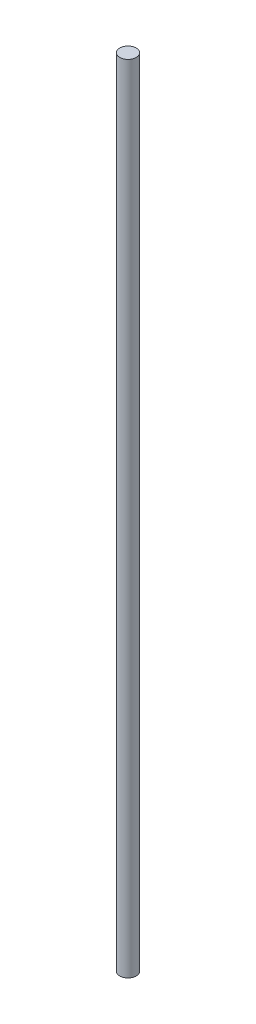
SolidWorks part; units mm, degrees
material "Alloy Steel"
ref_plane "Front Plane" through (0, 0, 0) normal (0, 0, 1) x (1, 0, 0)
ref_plane "Top Plane" through (0, 0, 0) normal (0, 1, 0) x (1, 0, 0)
ref_plane "Right Plane" through (0, 0, 0) normal (1, 0, 0) x (0, 0, -1)
sketch "Sketch1" plane through (0, 0, 0) normal (0, 1, 0) x (1, 0, 0)
  circle A0 centre (0, 0) radius 4.125
  dimension "D1" = 8.25
extrude "Boss-Extrude1" add sketch "Sketch1" along normal blind 400
